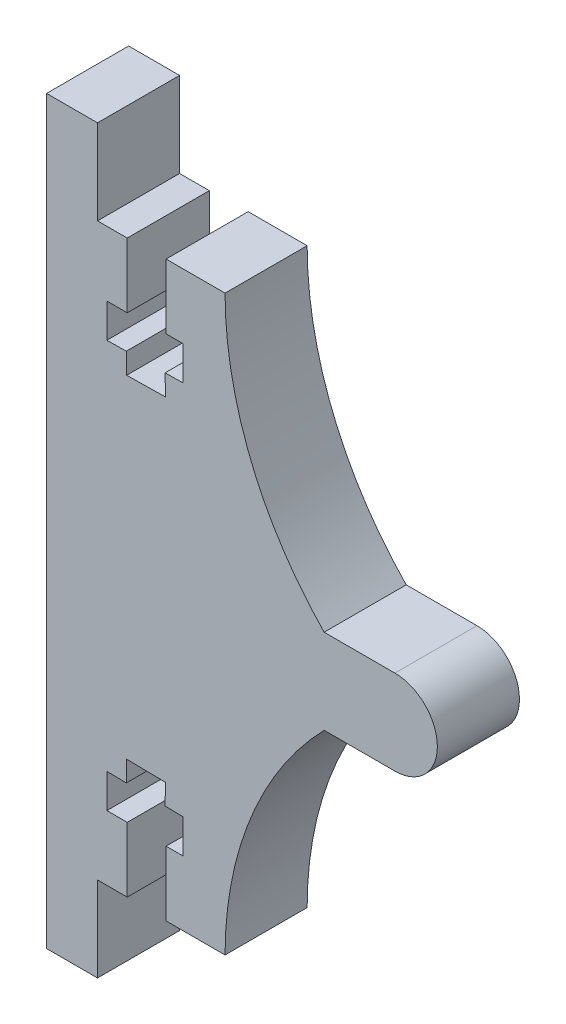
SolidWorks part; units mm, degrees
ref_plane "Front Plane" through (0, 0, 0) normal (0, 0, 1) x (1, 0, 0)
ref_plane "Top Plane" through (0, 0, 0) normal (0, 1, 0) x (1, 0, 0)
ref_plane "Right Plane" through (0, 0, 0) normal (1, 0, 0) x (0, 0, -1)
sketch "Sketch1" plane through (0, 0, 0) normal (0, 0, 1) x (1, 0, 0)
  line L0 (640.8999, 447.603) -> (645.8999, 447.603)
  line L1 (640.8999, 447.603) -> (640.8999, 441.603) construction
  line L2 (633.8999, 464.853) -> (633.8999, 424.353) construction
  line L3 (629.7324, 424.353) -> (633.8999, 424.353)
  line L4 (629.7324, 428.9289) -> (629.7324, 424.353)
  line L5 (630.9448, 428.9289) -> (629.7324, 428.9289)
  line L6 (630.9425, 431.3289) -> (630.9448, 428.9289)
  line L7 (629.6647, 431.3494) -> (630.9425, 431.3289)
  line L8 (629.6882, 432.8136) -> (629.6647, 431.3494)
  line L9 (626.9469, 432.8575) -> (629.6882, 432.8136)
  line L10 (626.9234, 431.3934) -> (626.9469, 432.8575)
  line L11 (625.5484, 431.4154) -> (626.9234, 431.3934)
  line L12 (625.5507, 429.0154) -> (625.5484, 431.4154)
  line L13 (626.9883, 429.0154) -> (625.5507, 429.0154)
  line L14 (626.9883, 424.4395) -> (626.9883, 429.0154)
  line L15 (624.8883, 424.4395) -> (626.9883, 424.4395)
  line L16 (624.8883, 418.4395) -> (624.8883, 424.4395)
  line L17 (621.2883, 464.7665) -> (621.2883, 470.7665)
  line L18 (621.2883, 470.7665) -> (624.8883, 470.7665)
  line L19 (624.8883, 470.7665) -> (624.8883, 464.7665)
  line L20 (624.8883, 464.7665) -> (626.9883, 464.7665)
  line L21 (626.9883, 464.7665) -> (626.9883, 460.1906)
  line L22 (626.9883, 460.1906) -> (625.5507, 460.1906)
  line L23 (625.5507, 460.1906) -> (625.5484, 457.7905)
  line L24 (625.5484, 457.7905) -> (626.9234, 457.8126)
  line L25 (626.9234, 457.8126) -> (626.9469, 456.3484)
  line L26 (626.9469, 456.3484) -> (629.6882, 456.3924)
  line L27 (629.6882, 456.3924) -> (629.6647, 457.8565)
  line L28 (629.6647, 457.8565) -> (630.9425, 457.877)
  line L29 (630.9425, 457.877) -> (630.9448, 460.2771)
  line L30 (630.9448, 460.2771) -> (629.7324, 460.2771)
  line L31 (629.7324, 460.2771) -> (629.7324, 464.853)
  line L32 (629.7324, 464.853) -> (633.8999, 464.853)
  line L33 (621.2883, 418.4395) -> (624.8883, 418.4395)
  line L34 (-348.8277, 444.603) -> (49651.1723, 444.603) construction
  line L36 (621.2883, 424.4395) -> (621.2883, 418.4395)
  line L38 (640.8999, 441.603) -> (645.8999, 441.603)
  line L39 (621.2883, 464.7665) -> (621.2883, 424.4395)
  arc A0 (645.8999, 447.603) -> (645.8999, 441.603) centre (645.8999, 444.603) cw
  arc A1 (633.8999, 464.853) -> (640.8999, 447.603) centre (658.6543, 464.853) ccw
  arc A2 (633.8999, 424.353) -> (640.8999, 441.603) centre (658.6543, 424.353) cw
  point P7 (640.8999, 444.603)
  dimension "D1" = 6
  dimension "D2" = 3.6
  dimension "D3" = 40.5
  dimension "D4" = 6
  dimension "D5" = 5
  dimension "D6" = 7
  dimension "D7" = 2.1
extrude "Boss-Extrude1" add sketch "Sketch1" along normal blind 5.8
